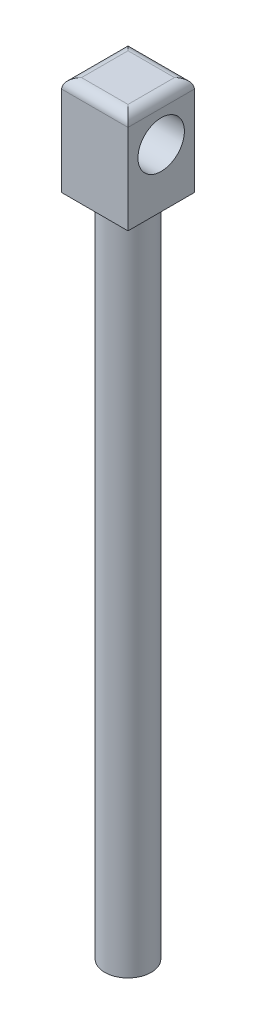
SolidWorks part; units mm, degrees
ref_plane "Front Plane" through (0, 0, 0) normal (0, 0, 1) x (1, 0, 0)
ref_plane "Top Plane" through (0, 0, 0) normal (0, 1, 0) x (1, 0, 0)
ref_plane "Right Plane" through (0, 0, 0) normal (1, 0, 0) x (0, 0, -1)
sketch "Sketch1" plane through (0, 0, 0) normal (0, 1, 0) x (1, 0, 0)
  circle A0 centre (0, 0) radius 17.78
extrude "Boss-Extrude1" add sketch "Sketch1" along normal blind 508 contours A0
sketch "Sketch2" plane through (0, 508, 0) normal (0, 1, 0) x (1, 0, 0)
  line L1 (-25.4, -25.4) -> (25.4, -25.4)
  line L2 (-25.4, -25.4) -> (-25.4, 25.4)
  line L3 (-25.4, 25.4) -> (25.4, 25.4)
  line L4 (25.4, -25.4) -> (25.4, 25.4)
  line L5 (-25.4, -25.4) -> (25.4, 25.4) construction
  line L6 (-25.4, 25.4) -> (25.4, -25.4) construction
  point P0 (0, 0)
extrude "Boss-Extrude2" add sketch "Sketch2" along normal blind 76.2
sketch "Sketch4" plane through (-25.4, 0, 0) normal (-1, 0, 0) x (0, 0, 1)
  circle A0 centre (0, 552.5014) radius 17.78
  dimension "D1" = 35.56
extrude "Cut-Extrude1" cut sketch "Sketch4" against normal through all
fillet "Fillet1" radius 7.62 4 edges at (25.4, 584.2, 0) (0, 584.2, -25.4) (-25.4, 584.2, 0) (0, 584.2, 25.4)
scale "Scale1" scale about centroid uniform scaling yes scale factor 2
